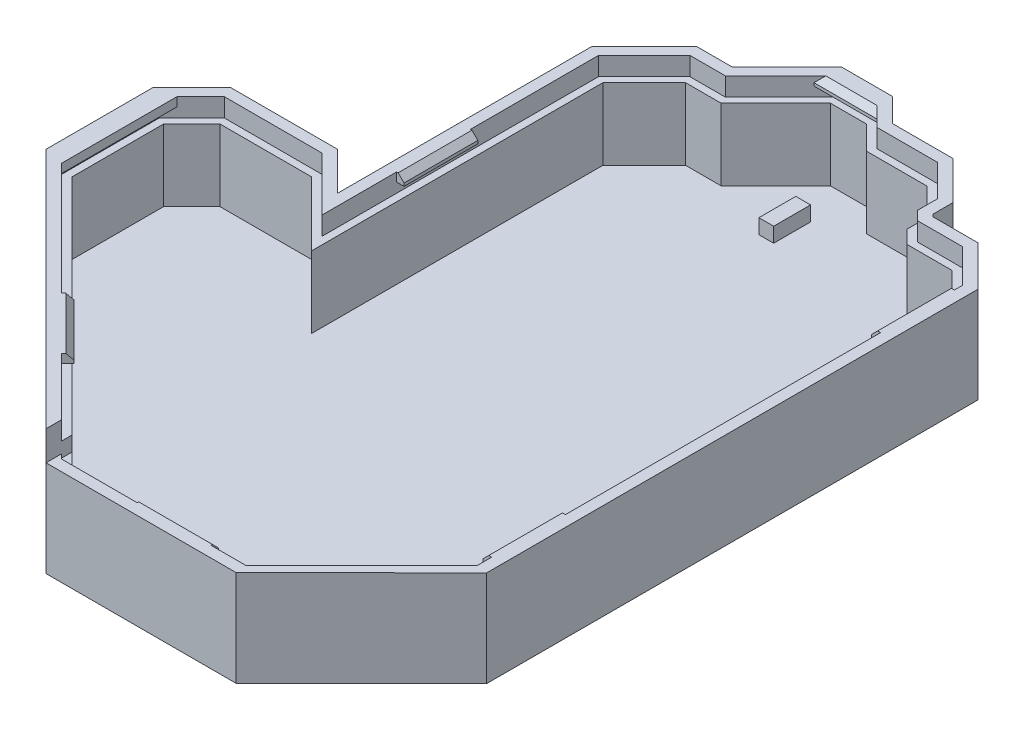
SolidWorks part; units mm, degrees
ref_plane "Plano frontal" through (0, 0, 0) normal (0, 0, 1) x (1, 0, 0)
ref_plane "Plano superior" through (0, 0, 0) normal (0, 1, 0) x (1, 0, 0)
ref_plane "Plano direito" through (0, 0, 0) normal (1, 0, 0) x (0, 0, -1)
sketch "Esboço1" plane through (0, 0, 0) normal (0, 1, 0) x (1, 0, 0)
  line L1 (-53.9394, 50.6061) -> (46.0606, 50.6061)
  line L2 (-53.9394, 50.6061) -> (-53.9394, -69.3939)
  line L3 (-53.9394, -69.3939) -> (46.0606, -69.3939)
  line L4 (46.0606, 50.6061) -> (46.0606, -69.3939)
  dimension "D1" = 120
  dimension "D2" = 100
extrude "Ressalto-extrusão1" add sketch "Esboço1" along normal blind 13
sketch "Esboço2" plane through (0, 13, 0) normal (0, 1, 0) x (1, 0, 0)
  line L0 (12.9941, -148.2893) -> (234.3275, -148.2893) construction
  line L1 (31.5082, -39.919) -> (31.5082, 24.595)
  line L2 (31.5082, 24.595) -> (27.5307, 28.5725)
  line L3 (27.5307, 28.5725) -> (21.4315, 28.5725)
  line L4 (21.4315, 28.5725) -> (19.6523, 30.3517)
  line L5 (19.6523, 30.3517) -> (19.6523, 33.082)
  line L6 (19.6523, 33.082) -> (15.9608, 36.7736)
  line L7 (15.9608, 36.7736) -> (7.7461, 36.7736)
  line L8 (7.7461, 36.7736) -> (4.5593, 39.9605)
  line L9 (4.5593, 39.9605) -> (-0.3211, 39.9605)
  line L10 (-0.3211, 39.9605) -> (-7.7304, 32.5512)
  line L11 (-7.7304, 32.5512) -> (-12.5302, 32.5512)
  line L12 (-12.5302, 32.5512) -> (-18.1457, 26.9357)
  line L13 (-18.1457, 26.9357) -> (-18.1457, -12.5386)
  line L14 (-18.1457, -12.5386) -> (-26.8394, -3.845)
  line L15 (-26.8394, -3.845) -> (-39.2461, -3.845)
  line L16 (-39.2461, -3.845) -> (-43.0632, -7.662)
  line L17 (-43.0632, -7.662) -> (-43.0632, -20.0687)
  line L18 (-43.0632, -20.0687) -> (-7.7304, -55.4015)
  line L19 (-7.7304, -55.4015) -> (15.9608, -55.4015)
  line L20 (15.9608, -55.4015) -> (31.5082, -39.919)
extrude "Corte-extrusão1" cut sketch "Esboço2" against normal blind 12.2
sketch "Esboço5" plane through (0, 13, 0) normal (0, 1, 0) x (1, 0, 0)
  line L0 (-406.7117, 39.0803) -> (-134.045, 39.0803) construction
  line L4 (34.0082, 16.2647) -> (34.0082, 25.6306)
  line L5 (34.0082, 25.6306) -> (28.5663, 31.0725)
  line L6 (28.5663, 31.0725) -> (22.4671, 31.0725)
  line L7 (22.4671, 31.0725) -> (22.1523, 31.3872)
  line L8 (22.1523, 31.3872) -> (22.1523, 34.1176)
  line L9 (22.1523, 34.1176) -> (16.9963, 39.2736)
  line L10 (16.9963, 39.2736) -> (8.7817, 39.2736)
  line L11 (8.7817, 39.2736) -> (5.5948, 42.4605)
  line L12 (5.5948, 42.4605) -> (-1.3566, 42.4605)
  line L13 (-1.3566, 42.4605) -> (-8.7659, 35.0512)
  line L14 (-8.7659, 35.0512) -> (-13.5658, 35.0512)
  line L15 (-13.5658, 35.0512) -> (-20.6457, 27.9712)
  line L16 (-20.6457, 27.9712) -> (-20.6457, -6.5031)
  line L17 (-20.6457, -6.5031) -> (-25.8039, -1.345)
  line L18 (-25.8039, -1.345) -> (-40.2817, -1.345)
  line L19 (-40.2817, -1.345) -> (-45.5632, -6.6265)
  line L20 (-45.5632, -6.6265) -> (-45.5632, -21.1043)
  line L21 (-45.5632, -21.1043) -> (-8.7659, -57.9015)
  line L22 (-8.7659, -57.9015) -> (9.2056, -57.9015)
  line L25 (34.0082, -40.9576) -> (34.0082, 16.2647)
  line L26 (31.5082, -39.919) -> (31.5082, 24.595) construction
  line L27 (-53.9394, 50.6061) -> (46.0606, 50.6061)
  line L28 (-53.9394, 50.6061) -> (-53.9394, -69.3939)
  line L29 (-53.9394, -69.3939) -> (46.0606, -69.3939)
  line L30 (46.0606, 50.6061) -> (46.0606, -69.3939)
  line L31 (31.5082, 24.595) -> (27.5307, 28.5725) construction
  line L32 (27.5307, 28.5725) -> (21.4315, 28.5725) construction
  line L33 (21.4315, 28.5725) -> (19.6523, 30.3517) construction
  line L34 (19.6523, 30.3517) -> (19.6523, 33.082) construction
  line L35 (19.6523, 33.082) -> (15.9608, 36.7736) construction
  line L36 (15.9608, 36.7736) -> (7.7461, 36.7736) construction
  line L37 (7.7461, 36.7736) -> (4.5593, 39.9605) construction
  line L38 (4.5593, 39.9605) -> (-0.3211, 39.9605) construction
  line L39 (-0.3211, 39.9605) -> (-7.7304, 32.5512) construction
  line L40 (-7.7304, 32.5512) -> (-12.5302, 32.5512) construction
  line L41 (-12.5302, 32.5512) -> (-18.1457, 26.9357) construction
  line L42 (-18.1457, 26.9357) -> (-18.1457, -12.5386) construction
  line L43 (-18.1457, -12.5386) -> (-26.8394, -3.845) construction
  line L44 (-26.8394, -3.845) -> (-39.2461, -3.845) construction
  line L45 (-39.2461, -3.845) -> (-43.0632, -7.662) construction
  line L46 (-43.0632, -7.662) -> (-43.0632, -20.0687) construction
  line L47 (-43.0632, -20.0687) -> (-7.7304, -55.4015) construction
  line L48 (-7.7304, -55.4015) -> (15.9608, -55.4015) construction
  line L53 (34.0082, -40.9576) -> (16.9932, -57.9015)
  line L54 (16.9932, -57.9015) -> (9.2056, -57.9015)
  line L55 (15.9608, -55.4015) -> (31.5082, -39.919) construction
  point P38 (20.5419, 29.4621)
  point P39 (22.1523, 32.7524)
  dimension "D1" = 2.5
  dimension "D2" = 2.5
  dimension "D3" = 2.5
  dimension "D4" = 2.5
  dimension "D5" = 2.5
  dimension "D6" = 2.5
  dimension "D7" = 2.5
  dimension "D8" = 2.5
  dimension "D9" = 2.5
  dimension "D10" = 2.5
  dimension "D11" = 2.5
  dimension "D12" = 2.5
  dimension "D13" = 2.5
  dimension "D14" = 2.5
  dimension "D15" = 2.5
  dimension "D16" = 2.5
  dimension "D17" = 2.5
  dimension "D18" = 2.5
  dimension "D19" = 2.5
  dimension "D20" = 2.5
extrude "Corte-extrusão2" cut sketch "Esboço5" against normal blind 24
sketch "Esboço6" plane through (0, 13, 0) normal (0, 1, 0) x (1, 0, 0)
  line L0 (-26.4252, -2.845) -> (-19.1457, -10.1244)
  line L1 (-19.1457, 27.3499) -> (-12.9445, 33.5512)
  line L2 (-12.9445, 33.5512) -> (-8.1446, 33.5512)
  line L3 (-8.1446, 33.5512) -> (-0.7353, 40.9605)
  line L4 (-0.7353, 40.9605) -> (4.9735, 40.9605)
  line L5 (4.9735, 40.9605) -> (8.1604, 37.7736)
  line L6 (8.1604, 37.7736) -> (16.375, 37.7736)
  line L7 (16.375, 37.7736) -> (20.6523, 33.4963)
  line L8 (20.6523, 33.4963) -> (20.6523, 30.7659)
  line L9 (20.6523, 30.7659) -> (21.8458, 29.5725)
  line L10 (21.8458, 29.5725) -> (27.945, 29.5725)
  line L11 (27.945, 29.5725) -> (32.5082, 25.0092)
  line L12 (32.5082, 25.0092) -> (32.5082, -40.7081)
  line L13 (32.5082, -40.7081) -> (16.8148, -56.4015)
  line L14 (16.8148, -56.4015) -> (-8.1446, -56.4015)
  line L15 (-8.1446, -56.4015) -> (-44.0632, -20.4829)
  line L16 (-44.0632, -20.4829) -> (-44.0632, -7.2478)
  line L17 (-44.0632, -7.2478) -> (-39.6603, -2.845)
  line L18 (-39.6603, -2.845) -> (-26.4252, -2.845)
  line L19 (-18.1457, -12.5386) -> (-26.8394, -3.845) construction
  line L20 (-19.1457, 27.3499) -> (-19.1457, -10.1244)
  line L21 (-26.8394, -3.845) -> (-39.2461, -3.845) construction
  line L22 (-43.0632, -7.662) -> (-43.0632, -20.0687) construction
  line L23 (-39.2461, -3.845) -> (-43.0632, -7.662) construction
  line L24 (-43.0632, -20.0687) -> (-7.7304, -55.4015) construction
  line L25 (-7.7304, -55.4015) -> (15.9608, -55.4015) construction
  line L27 (31.5082, -39.919) -> (31.5082, 24.595) construction
  line L29 (-18.1457, 26.9357) -> (-18.1457, -12.5386) construction
  line L30 (-12.5302, 32.5512) -> (-18.1457, 26.9357) construction
  line L31 (-7.7304, 32.5512) -> (-12.5302, 32.5512) construction
  line L32 (-0.3211, 39.9605) -> (-7.7304, 32.5512) construction
  line L33 (4.5593, 39.9605) -> (-0.3211, 39.9605) construction
  line L34 (7.7461, 36.7736) -> (4.5593, 39.9605) construction
  line L35 (15.9608, 36.7736) -> (7.7461, 36.7736) construction
  line L36 (19.6523, 33.082) -> (15.9608, 36.7736) construction
  line L37 (19.6523, 30.3517) -> (19.6523, 33.082) construction
  line L38 (21.4315, 28.5725) -> (19.6523, 30.3517) construction
  line L39 (27.5307, 28.5725) -> (21.4315, 28.5725) construction
  line L40 (31.5082, 24.595) -> (27.5307, 28.5725) construction
  point P26 (-41.8618, -5.0464)
  point P53 (19.6523, 31.7169)
  dimension "D1" = 1
  dimension "D2" = 1
  dimension "D3" = 1
  dimension "D4" = 1
  dimension "D5" = 1
  dimension "D6" = 1
  dimension "D7" = 1
  dimension "D8" = 1
  dimension "D9" = 1
  dimension "D10" = 1
  dimension "D11" = 1
  dimension "D12" = 1
  dimension "D13" = 1
  dimension "D14" = 1
  dimension "D15" = 1
  dimension "D16" = 1
  dimension "D17" = 1
  dimension "D18" = 1
  dimension "D19" = 1
extrude "Corte-extrusão3" cut sketch "Esboço6" against normal blind 2.5
sketch "Esboço7" plane through (0, 13, 0) normal (0, 1, 0) x (1, 0, 0)
  line L0 (-19.1457, 27.3499) -> (-19.1457, -10.1244) construction
  line L5 (-19.1457, 0) -> (-18.1457, 0)
  line L10 (-19.1457, 0) -> (-19.1457, 10)
  line L11 (32.5082, -40.7081) -> (32.5082, 25.0092) construction
  line L16 (32.5082, -38.7758) -> (31.3082, -38.7758)
  line L17 (-19.1457, 10) -> (-18.1457, 10)
  line L22 (-18.1457, 0) -> (-18.1457, 10)
  line L23 (32.5082, -38.7758) -> (32.5082, -28.7758)
  line L32 (32.5082, -40.7081) -> (32.5082, 25.0092) construction
  line L53 (32.5082, 23.9262) -> (31.3082, 23.9262)
  line L54 (32.5082, 23.9262) -> (32.5082, 13.9262)
  line L55 (32.5082, 13.9262) -> (31.3082, 13.9262)
  line L56 (31.3082, 23.9262) -> (31.3082, 13.9262)
  line L57 (32.5082, -28.7758) -> (31.3082, -28.7758)
  line L58 (31.3082, -38.7758) -> (31.3082, -28.7758)
  line L59 (-8.1446, -56.4015) -> (16.8148, -56.4015) construction
  line L60 (2.0868, -56.4015) -> (12.0868, -56.4015)
  line L61 (2.0868, -56.4015) -> (2.0868, -55.4015)
  line L62 (2.0868, -55.4015) -> (12.0868, -55.4015)
  line L63 (12.0868, -56.4015) -> (12.0868, -55.4015)
  line L64 (-18.1457, 26.9357) -> (-18.1457, -12.5386) construction
  line L65 (-42.8699, -5.7704) -> (-44.0699, -5.7704)
  line L66 (-42.8699, -5.7704) -> (-42.8699, -22.211)
  line L67 (-42.8699, -22.211) -> (-44.0699, -22.211)
  line L68 (-44.0699, -5.7704) -> (-44.0699, -22.211)
  line L69 (-27.6071, -36.939) -> (-20.536, -44.0101)
  line L74 (-44.0632, -20.4829) -> (-8.1446, -56.4015) construction
  line L75 (-44.0632, -20.4829) -> (-8.1446, -56.4015) construction
  line L76 (-20.536, -44.0101) -> (-19.6875, -43.1616)
  line L77 (-19.6875, -43.1616) -> (-26.7586, -36.0905)
  line L78 (-26.7586, -36.0905) -> (-27.6071, -36.939)
  line L79 (8.1604, 37.7736) -> (4.9735, 40.9605) construction
  line L80 (6.3803, 39.5536) -> (-2.2158, 39.5536)
  line L81 (6.3803, 39.5536) -> (6.3803, 40.9605)
  line L82 (6.3803, 40.9605) -> (-2.2158, 40.9605)
  line L83 (-2.2158, 39.5536) -> (-2.2158, 40.9605)
  point P15 (31.9082, 13.9262)
  dimension "D2" = 10
  dimension "D3" = 1
  dimension "D4" = 1.2
  dimension "D5" = 1.2
  dimension "D6" = 10
  dimension "D7" = 10
  dimension "D8" = 10
  dimension "D9" = 10
  dimension "D10" = 1.2
  dimension "D13" = 1.2
extrude "Ressalto-extrusão2" add sketch "Esboço7" against normal blind 1.2
sketch "Esboço8" plane through (0, 0, 57.9015) normal (0, 0, 1) x (1, 0, 0)
  line L5 (-8.7659, 13) -> (-12.7659, 13)
  line L6 (-8.7659, 13) -> (-8.7659, 8.5)
  line L7 (-8.7659, 8.5) -> (-12.7659, 8.5)
  line L8 (-12.7659, 13) -> (-12.7659, 8.5)
  dimension "D1" = 4.5
  dimension "D2" = 4
extrude "Corte-extrusão4" cut sketch "Esboço8" against normal blind 10
sketch "Esboço9" plane through (0, 0.8, 0) normal (0, 1, 0) x (1, 0, 0)
  line L1 (0.5707, 34.3751) -> (2.5707, 34.3751)
  line L2 (0.5707, 34.3751) -> (0.5707, 29.3751)
  line L3 (0.5707, 29.3751) -> (2.5707, 29.3751)
  line L4 (2.5707, 34.3751) -> (2.5707, 29.3751)
  dimension "D1" = 2
  dimension "D2" = 5
extrude "Ressalto-extrusão3" add sketch "Esboço9" along normal blind 2
chamfer "Chanfro1" distance 0.8 angle 45 6 edges at (7.0868, 13, 55.4015) (31.3082, 13, 33.7758) (-23.223, 13, 39.626) (31.3082, 13, -18.9262) (-18.1457, 13, -5) (2.1191, 13, -39.5536)
